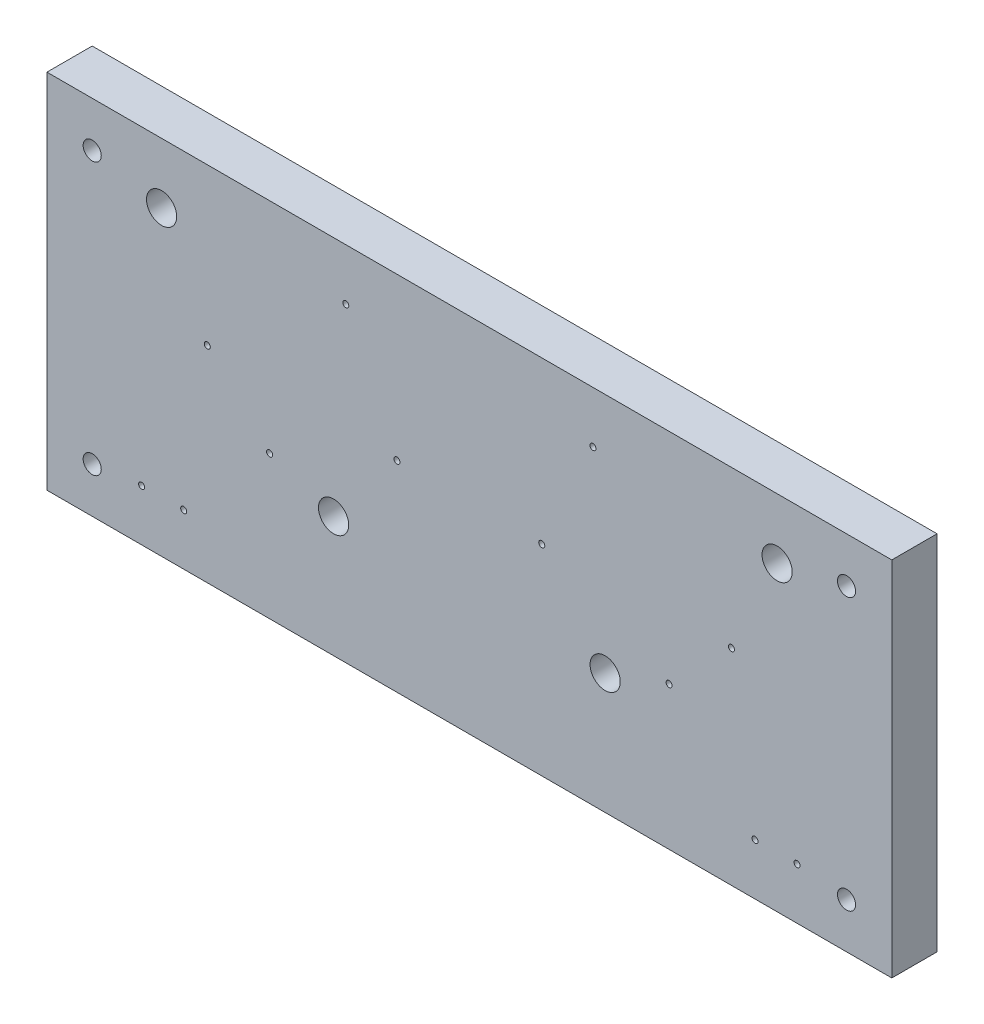
SolidWorks part; units mm, degrees
ref_plane "Front Plane" through (0, 0, 0) normal (0, 0, 1) x (1, 0, 0)
ref_plane "Top Plane" through (0, 0, 0) normal (0, 1, 0) x (1, 0, 0)
ref_plane "Right Plane" through (0, 0, 0) normal (1, 0, 0) x (0, 0, -1)
sketch "Sketch1" plane through (0, 0, 0) normal (0, 0, 1) x (1, 0, 0)
  line L1 (-140, -60) -> (140, -60)
  line L2 (-140, -60) -> (-140, 60)
  line L3 (-140, 60) -> (140, 60)
  line L4 (140, -60) -> (140, 60)
  circle A0 centre (-125, 45) radius 3
  circle A1 centre (125, 45) radius 3
  circle A2 centre (125, -45) radius 3
  circle A3 centre (-125, -45) radius 3
  point P0 (0, 0)
  dimension "D1" = 2
  dimension "D2" = 2
extrude "Boss-Extrude1" add sketch "Sketch1" along normal blind 15
sketch "Sketch2" plane through (0, 0, 15) normal (0, 0, 1) x (1, 0, 0)
  circle A0 centre (-45, -20) radius 5
  circle A14 centre (-45, -20) radius 5
  circle A15 centre (45, -20) radius 5
  circle A16 centre (-102, 40) radius 5
  circle A17 centre (102, 40) radius 5
  circle A18 centre (-108.6069, -43) radius 1
  circle A19 centre (-66.2039, -12.5278) radius 1
  circle A20 centre (-94.67, -43) radius 1
  circle A21 centre (-23.9979, 6.5276) radius 1
  circle A22 centre (23.9912, 6.5276) radius 1
  circle A23 centre (66.1973, -12.5278) radius 1
  circle A24 centre (94.6633, -43) radius 1
  circle A25 centre (86.8541, 8.1426) radius 1
  circle A26 centre (40.9546, 42.9056) radius 1
  circle A27 centre (-40.9612, 42.9056) radius 1
  circle A28 centre (-86.8607, 8.1426) radius 1
  circle A29 centre (108.6002, -43) radius 1
  point P0 (0, 0)
extrude "Cut-Extrude1" cut sketch "Sketch2" against normal blind 30 contours A17 | A15 | A0 | A16 | A29 | A24 | A25 | A23 | A22 | A26 | A21 | A27 | A28 | A19 | A18 | A20
